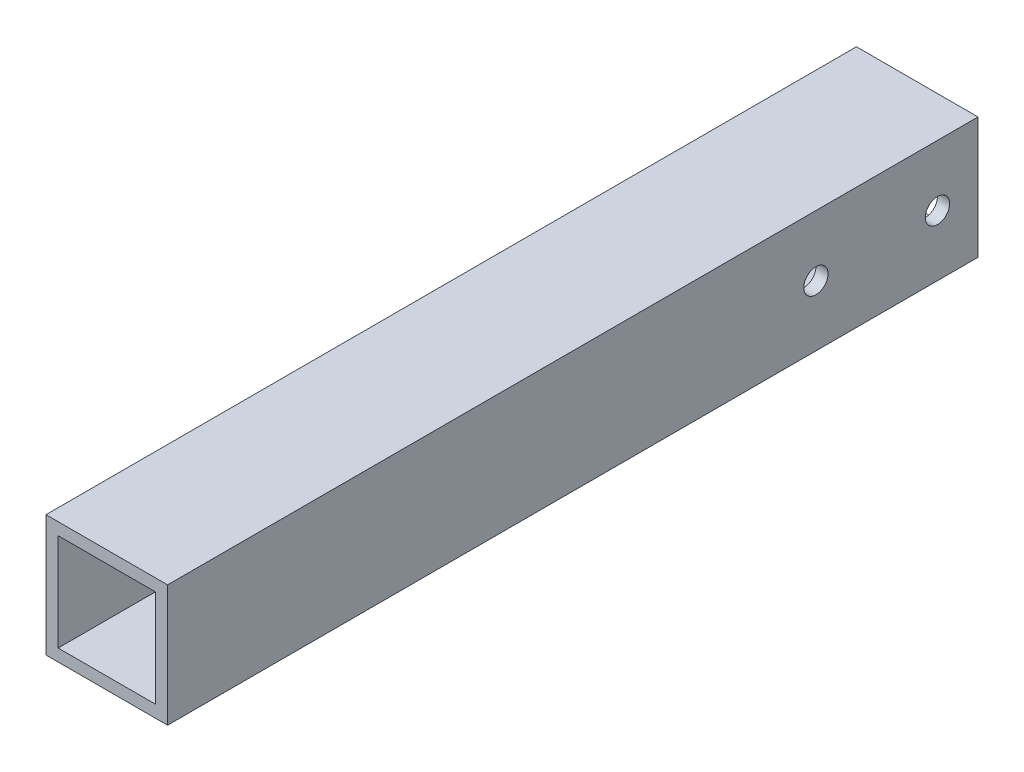
SolidWorks part; units mm, degrees
ref_plane "Plan de face" through (0, 0, 0) normal (0, 0, 1) x (1, 0, 0)
ref_plane "Plan de dessus" through (0, 0, 0) normal (0, 1, 0) x (1, 0, 0)
ref_plane "Plan de droite" through (0, 0, 0) normal (1, 0, 0) x (0, 0, -1)
sketch "Esquisse1" plane through (0, 0, 0) normal (0, 0, 1) x (1, 0, 0)
  line L1 (-7.5, -7.5) -> (7.5, -7.5)
  line L2 (-7.5, -7.5) -> (-7.5, 7.5)
  line L3 (-7.5, 7.5) -> (7.5, 7.5)
  line L4 (7.5, -7.5) -> (7.5, 7.5)
  line L5 (-7.5, -7.5) -> (7.5, 7.5) construction
  line L6 (-7.5, 7.5) -> (7.5, -7.5) construction
  point P0 (0, 0)
  dimension "D1" = 15
  dimension "D2" = 15
extrude "Extrusion1" add sketch "Esquisse1" along normal blind 100
sketch "Esquisse2" plane through (0, 0, 100) normal (0, 0, 1) x (1, 0, 0)
  line L0 (7.5, 7.5) -> (-7.5, 7.5) construction
  line L1 (-6, -6) -> (6, -6)
  line L2 (-6, -6) -> (-6, 6)
  line L3 (-6, 6) -> (6, 6)
  line L4 (6, -6) -> (6, 6)
  line L5 (-6, -6) -> (6, 6) construction
  line L6 (-6, 6) -> (6, -6) construction
  line L7 (7.5, -7.5) -> (7.5, 7.5) construction
  point P0 (0, 0)
  dimension "D1" = 1.5
  dimension "D2" = 1.5
extrude "Extrusion2" cut sketch "Esquisse2" against normal through all
sketch "Esquisse3" plane through (7.5, 0, 0) normal (1, 0, 0) x (0, 0, -1)
  circle A0 centre (-5, 0) radius 1.5
  dimension "D1" = 3
extrude "Enlèv. mat.-Extru.1" cut sketch "Esquisse3" against normal through all
sketch "Esquisse4" plane through (7.5, 0, 0) normal (1, 0, 0) x (0, 0, -1)
  circle A0 centre (-20, 0) radius 1.5
  dimension "D1" = 3
extrude "Enlèv. mat.-Extru.2" cut sketch "Esquisse4" against normal through all
